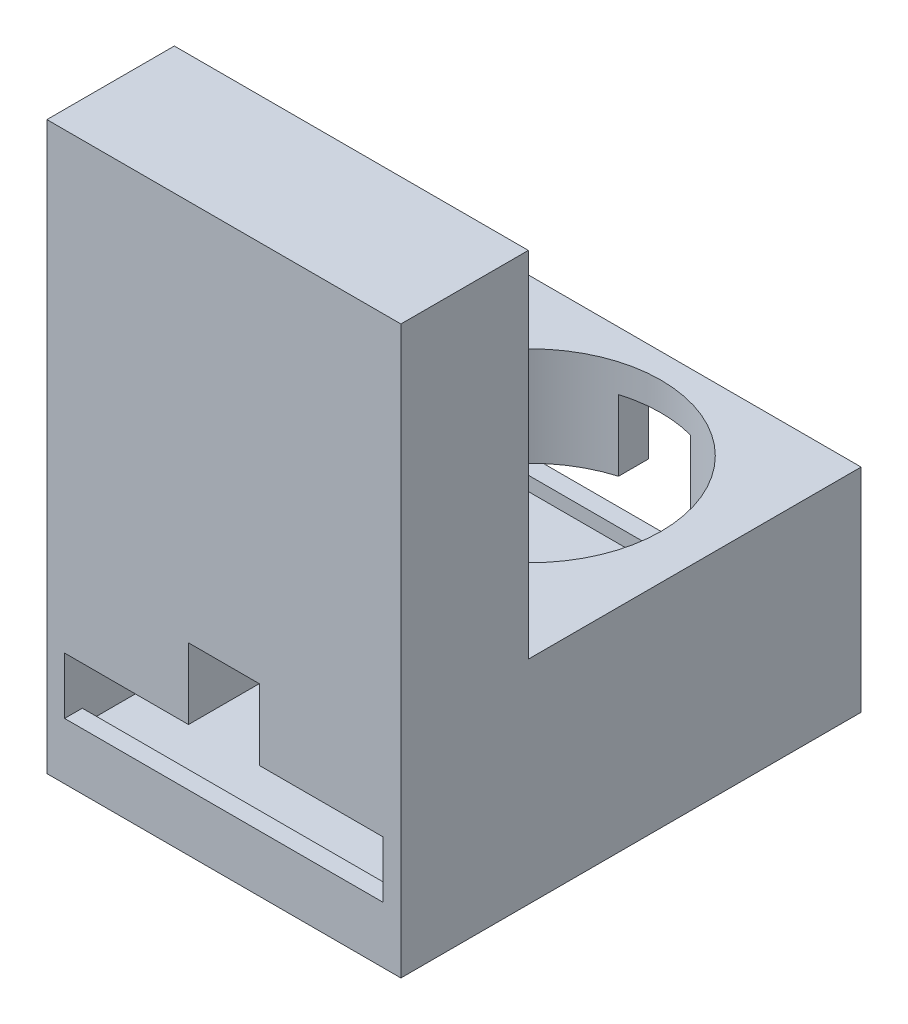
SolidWorks part; units mm, degrees
ref_plane "Front Plane" through (0, 0, 0) normal (0, 0, 1) x (1, 0, 0)
ref_plane "Top Plane" through (0, 0, 0) normal (0, 1, 0) x (1, 0, 0)
ref_plane "Right Plane" through (0, 0, 0) normal (1, 0, 0) x (0, 0, -1)
sketch "Sketch1" plane through (0, 0, 0) normal (0, 1, 0) x (1, 0, 0)
  line L1 (0, 0) -> (50, 0)
  line L2 (0, 0) -> (0, 65)
  line L3 (0, 65) -> (50, 65)
  line L4 (50, 0) -> (50, 65)
  dimension "D1" = 50
  dimension "D2" = 65
extrude "Boss-Extrude1" add sketch "Sketch1" along normal blind 30
sketch "Sketch3" plane through (0, 0, 0) normal (0, 0, 1) x (1, 0, 0)
  line L0 (0, 0) -> (50, 0) construction
  line L1 (2.5, 8) -> (47.5, 8)
  line L2 (2.5, 8) -> (2.5, 16)
  line L3 (2.5, 16) -> (47.5, 16)
  line L4 (47.5, 8) -> (47.5, 16)
  line L5 (25, 16) -> (25, 26) construction
  line L6 (20, 16) -> (30, 16)
  line L7 (20, 16) -> (20, 26)
  line L8 (20, 26) -> (30, 26)
  line L9 (30, 16) -> (30, 26)
  line L11 (25, 0) -> (25, 8) construction
  point P12 (25, 26)
  dimension "D1" = 8
  dimension "D2" = 8
  dimension "D3" = 10
  dimension "D4" = 10
  dimension "D5" = 45
extrude "Cut-Extrude4" cut sketch "Sketch3" against normal through all contours L3 L9 L8 L7 | L1 L4 L3 L2
sketch "Sketch4" plane through (47.5, 0, 0) normal (-1, 0, 0) x (0, 0, 1)
  line L0 (-65, 8) -> (0, 8) construction
  line L1 (-62.5, 8) -> (-2.5, 8)
  line L2 (-62.5, 8) -> (-62.5, 6)
  line L3 (-62.5, 6) -> (-2.5, 6)
  line L4 (-2.5, 8) -> (-2.5, 6)
  point P6 (-32.5, 8)
  point P7 (-32.5, 8)
  dimension "D1" = 60
  dimension "D2" = 2
extrude "Cut-Extrude5" cut sketch "Sketch4" along normal up to surface (45 mm away) up to face at (2.5, 12, -32.5)
sketch "Sketch5" plane through (0, 30, 0) normal (0, 1, 0) x (1, 0, 0)
  line L0 (50, 65) -> (0, 65) construction
  circle A0 centre (25.2445, 43) radius 18.5
  dimension "D1" = 37
  dimension "D2" = 22
extrude "Cut-Extrude6" cut sketch "Sketch5" against normal up to surface (14 mm away) up to face at (11.25, 16, -32.5)
sketch "Sketch6" plane through (0, 30, 0) normal (0, 1, 0) x (1, 0, 0)
  line L0 (50, 0) -> (50, 65) construction
  line L1 (0, 0) -> (50, 0)
  line L2 (0, 0) -> (0, 18)
  line L3 (0, 18) -> (50, 18)
  line L4 (50, 0) -> (50, 18)
  circle A0 centre (25.2445, 43) radius 18.5 construction
  dimension "D1" = 25
extrude "Boss-Extrude2" add sketch "Sketch6" along normal blind 50
